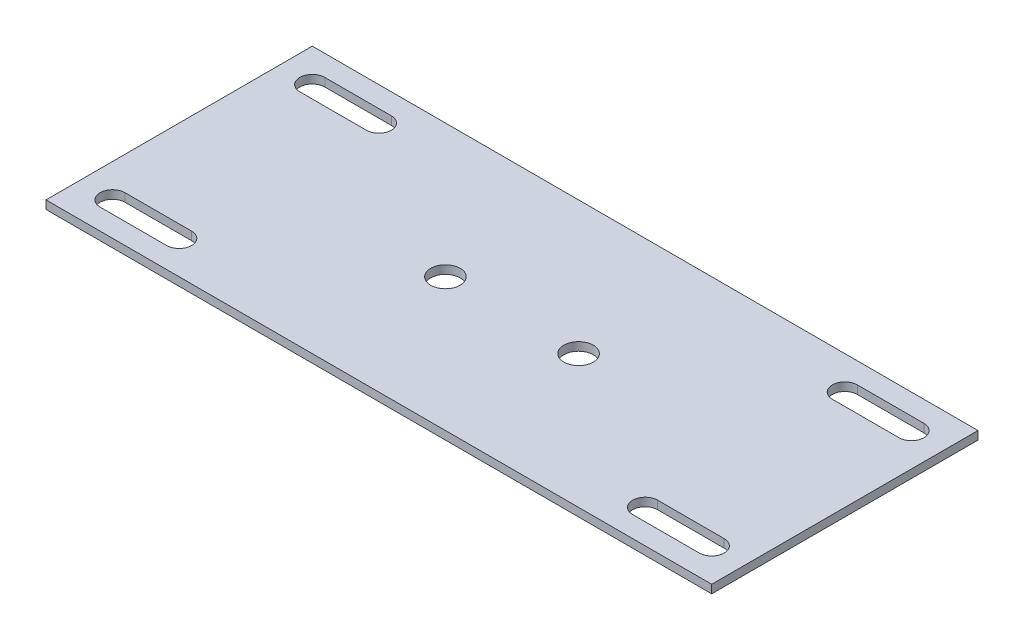
SolidWorks part; units mm, degrees
ref_plane "Front Plane" through (0, 0, 0) normal (0, 0, 1) x (1, 0, 0)
ref_plane "Top Plane" through (0, 0, 0) normal (0, 1, 0) x (1, 0, 0)
ref_plane "Right Plane" through (0, 0, 0) normal (1, 0, 0) x (0, 0, -1)
sketch "Sketch1" plane through (0, 0, 0) normal (0, 1, 0) x (1, 0, 0)
  line L1 (-63.5, -25.4) -> (63.5, -25.4)
  line L2 (-63.5, -25.4) -> (-63.5, 25.4)
  line L3 (-63.5, 25.4) -> (63.5, 25.4)
  line L4 (63.5, -25.4) -> (63.5, 25.4)
  line L5 (-63.5, -25.4) -> (63.5, 25.4) construction
  line L6 (-63.5, 25.4) -> (63.5, -25.4) construction
  point P0 (0, 0)
  dimension "D1" = 127
  dimension "D2" = 50.8
extrude "Boss-Extrude1" add sketch "Sketch1" along normal blind 1.5875
sketch "Sketch2" plane through (0, 1.5875, 0) normal (0, 1, 0) x (1, 0, 0)
  line L0 (-12.7, 0) -> (12.7, 0) construction
  line L1 (-57.15, 19.05) -> (-44.45, 19.05) construction
  line L2 (-57.15, 16.6687) -> (-44.45, 16.6687)
  line L3 (-57.15, 21.4312) -> (-44.45, 21.4312)
  line L4 (-57.15, -19.05) -> (-44.45, -19.05) construction
  line L5 (-57.15, -21.4313) -> (-44.45, -21.4313)
  line L6 (-57.15, -16.6688) -> (-44.45, -16.6688)
  line L7 (44.45, 19.05) -> (57.15, 19.05) construction
  line L8 (44.45, 16.6687) -> (57.15, 16.6687)
  line L9 (44.45, 21.4312) -> (57.15, 21.4312)
  line L10 (44.45, -19.05) -> (57.15, -19.05) construction
  line L11 (44.45, -21.4313) -> (57.15, -21.4313)
  line L12 (44.45, -16.6688) -> (57.15, -16.6688)
  line L14 (-57.15, -19.05) -> (57.15, -19.05) construction
  line L15 (-57.15, -19.05) -> (-57.15, 19.05) construction
  line L16 (-57.15, 19.05) -> (57.15, 19.05) construction
  line L17 (57.15, -19.05) -> (57.15, 19.05) construction
  line L18 (-57.15, -19.05) -> (57.15, 19.05) construction
  line L19 (-57.15, 19.05) -> (57.15, -19.05) construction
  circle A0 centre (-12.7, 0) radius 1.27
  circle A1 centre (12.7, 0) radius 1.27
  arc A2 (-57.15, 21.4312) -> (-57.15, 16.6687) centre (-57.15, 19.05) ccw
  arc A3 (-44.45, 16.6687) -> (-44.45, 21.4312) centre (-44.45, 19.05) ccw
  arc A4 (-57.15, -16.6688) -> (-57.15, -21.4313) centre (-57.15, -19.05) ccw
  arc A5 (-44.45, -21.4313) -> (-44.45, -16.6688) centre (-44.45, -19.05) ccw
  arc A6 (44.45, 21.4312) -> (44.45, 16.6687) centre (44.45, 19.05) ccw
  arc A7 (57.15, 16.6687) -> (57.15, 21.4312) centre (57.15, 19.05) ccw
  arc A8 (44.45, -16.6688) -> (44.45, -21.4313) centre (44.45, -19.05) ccw
  arc A9 (57.15, -21.4313) -> (57.15, -16.6688) centre (57.15, -19.05) ccw
  point P8 (0, 0)
  point P31 (0, 0)
  dimension "D1" = 25.4
  dimension "D2" = 2.54
  dimension "D3" = 12.7
  dimension "D4" = 4.7625
  dimension "D5" = 2.3812
  dimension "D9" = 2.3813
  dimension "D10" = 2.3813
  dimension "D6" = 12.7
  dimension "D7" = 12.7
  dimension "D8" = 12.7
  dimension "D11" = 38.1
  dimension "D12" = 114.3
extrude "Cut-Extrude1" cut sketch "Sketch2" against normal through all
hole_wizard "#10 Clearance Hole1" positions "Sketch4" profile "Sketch3" hole size "#10" standard "ANSI Inch" end condition through all
sketch "Sketch4" plane through (0, 1.5875, 0) normal (0, 1, 0) x (1, 0, 0)
  point P0 (-12.7, 0)
  point P3 (12.7, 0)
sketch "Sketch3" plane through (-12.7, 1.5875, 0) normal (1, 0, 0) x (0, 0, 1)
  line L0 (0, 0) -> (0, 1.5875)
  line L1 (0, 1.5875) -> (2.8067, 1.5875)
  line L2 (2.8067, 1.5875) -> (2.8067, 0)
  line L5 (2.8067, 0) -> (0, 0)
  line L11 (0, -6.35) -> (0, 107.95) construction
  dimension "Thru Hole Dia." = 5.6134
  dimension "Thru Hole Depth" = 1.5875
